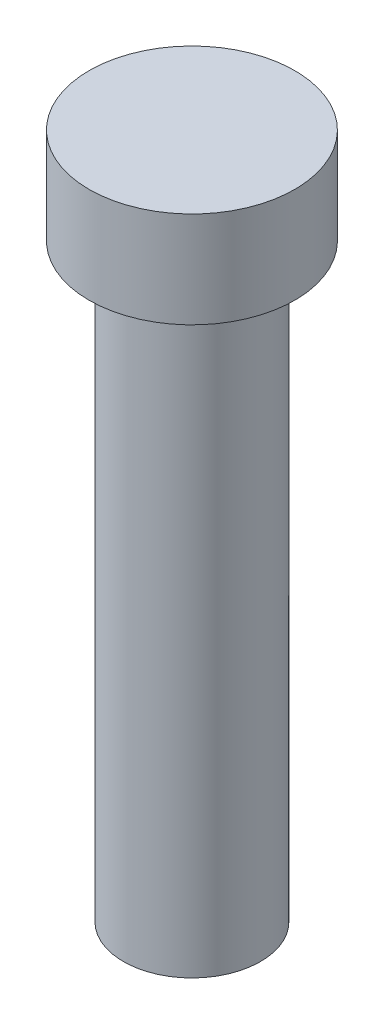
SolidWorks part; units mm, degrees
ref_plane "Front Plane" through (0, 0, 0) normal (0, 0, 1) x (1, 0, 0)
ref_plane "Top Plane" through (0, 0, 0) normal (0, 1, 0) x (1, 0, 0)
ref_plane "Right Plane" through (0, 0, 0) normal (1, 0, 0) x (0, 0, -1)
sketch "Sketch1" plane through (0, 0, 0) normal (0, 1, 0) x (1, 0, 0)
  circle A0 centre (0, 0) radius 7.5
  dimension "D1" = 15
extrude "Boss-Extrude1" add sketch "Sketch1" along normal blind 7
sketch "Sketch2" plane through (0, 0, 0) normal (0, -1, 0) x (1, 0, 0)
  circle A0 centre (0, 0) radius 5
  dimension "D1" = 10
extrude "Boss-Extrude2" add sketch "Sketch2" along normal blind 43
